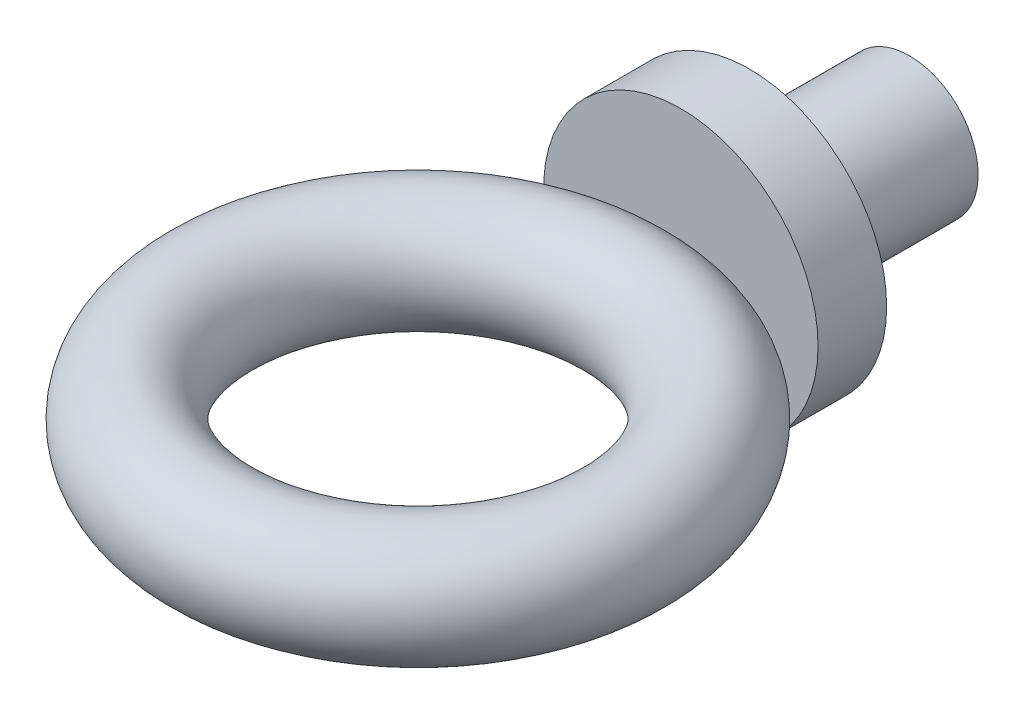
SolidWorks part; units mm, degrees
material "AISI Type 316L stainless steel"
ref_plane "Front Plane" through (0, 0, 0) normal (0, 0, 1) x (1, 0, 0)
ref_plane "Top Plane" through (0, 0, 0) normal (0, 1, 0) x (1, 0, 0)
ref_plane "Right Plane" through (0, 0, 0) normal (1, 0, 0) x (0, 0, -1)
sketch "Extrude sketch 1" plane through (0, 0, 0) normal (0, 0, 1) x (1, 0, 0)
  circle A0 centre (0, 0) radius 6
  dimension "D1" = 12
extrude "Extrude 1" add sketch "Extrude sketch 1" along normal blind 14.5 from offset 14 separate body
sketch "Extrude sketch 2" plane through (0, 0, 0) normal (0, 0, 1) x (1, 0, 0)
  circle A0 centre (0, 0) radius 12
  dimension "D1" = 24
extrude "Extrude 2" add sketch "Extrude sketch 2" along normal blind 6 separate body
sketch "Revolve profile 1" plane through (0, 0, 0) normal (0, 1, 0) x (1, 0, 0)
  line L0 (0, 10) -> (0, -10) construction
  circle A0 centre (18, 0) radius 5
  dimension "D1" = 10
  dimension "D2" = 18
revolve "Revolve 1" add sketch "Revolve profile 1" angle 360 about L0
move or copy body "Revolve rotate 1" bodies to move or copy 103 copy no rotation origin (0, 0, 0) rotation axis (1, 0, 0) rotation angle 90
move or copy body "Revolve place 1" bodies to move or copy 104 copy no translate (0, 0, 29) parameters "D1"=0, "D2"=0, "D3"=29
